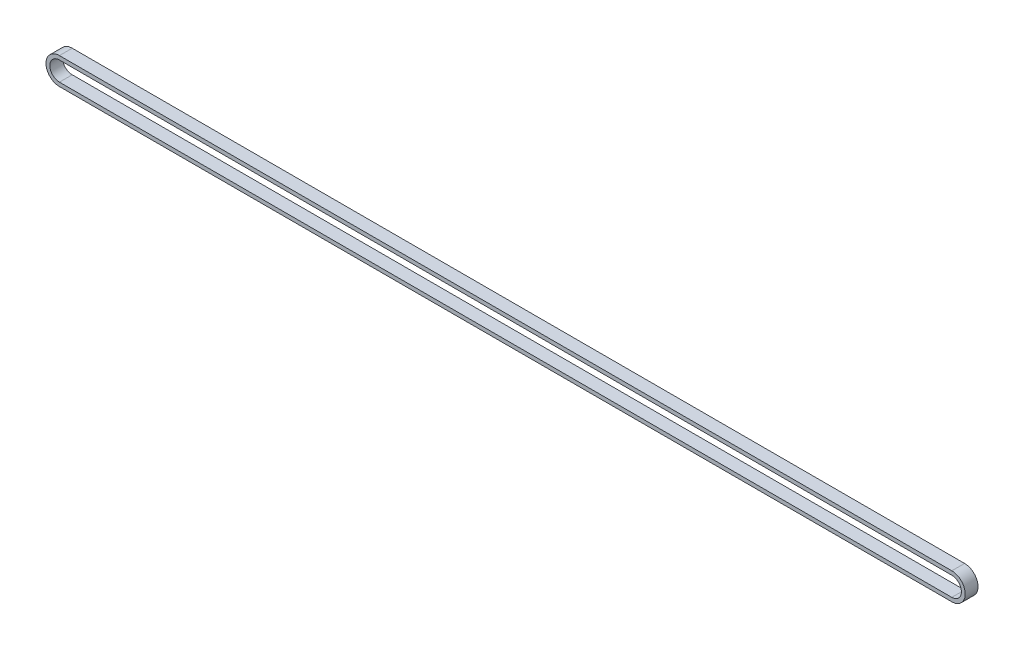
SolidWorks part; units mm, degrees
ref_plane "Front Plane" through (0, 0, 0) normal (0, 0, 1) x (1, 0, 0)
ref_plane "Top Plane" through (0, 0, 0) normal (0, 1, 0) x (1, 0, 0)
ref_plane "Right Plane" through (0, 0, 0) normal (1, 0, 0) x (0, 0, -1)
sketch "Sketch1" plane through (0, 0, 0) normal (0, 0, 1) x (1, 0, 0)
  line L0 (-209.395, 0) -> (209.395, 0) construction
  line L1 (-209.395, 4.5) -> (209.395, 4.5)
  line L2 (-209.395, -4.5) -> (209.395, -4.5)
  arc A0 (-209.395, 4.5) -> (-209.395, -4.5) centre (-209.395, 0) ccw
  arc A1 (209.395, -4.5) -> (209.395, 4.5) centre (209.395, 0) ccw
  point P2 (0, 0)
  dimension "D2" = 4.5
  dimension "D1" = 418.79
extrude "Extrude-Thin1" add sketch "Sketch1" along normal blind 6 thin thin type one direction wall 1.8
